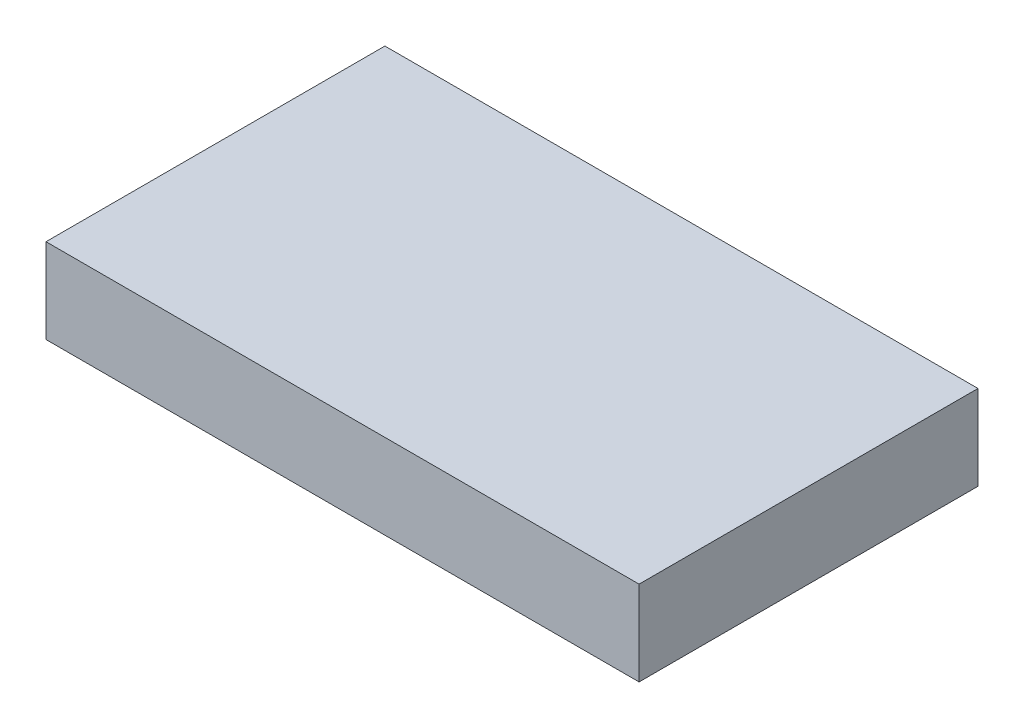
SolidWorks part; units mm, degrees
ref_plane "Front Plane" through (0, 0, 0) normal (0, 0, 1) x (1, 0, 0)
ref_plane "Top Plane" through (0, 0, 0) normal (0, 1, 0) x (1, 0, 0)
ref_plane "Right Plane" through (0, 0, 0) normal (1, 0, 0) x (0, 0, -1)
sketch "Sketch1" plane through (0, 0, 0) normal (0, 0, 1) x (1, 0, 0)
  line L1 (0, 0) -> (35, 0)
  line L2 (0, 0) -> (0, 5)
  line L3 (0, 5) -> (35, 5)
  line L4 (35, 0) -> (35, 5)
extrude "Boss-Extrude1" add sketch "Sketch1" along normal blind 20
